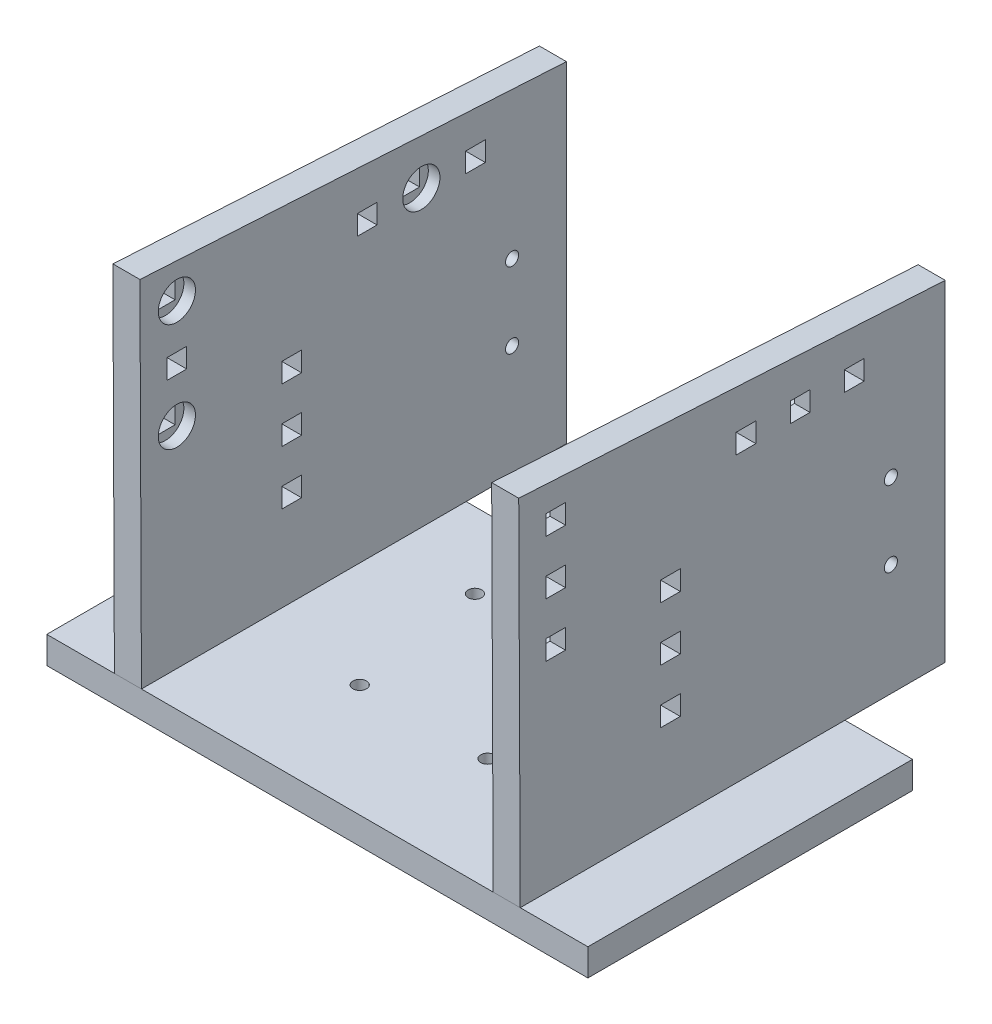
SolidWorks part; units mm, degrees
material "ABS"
ref_plane "Front Plane" through (0, 0, 0) normal (0, 0, 1) x (1, 0, 0)
ref_plane "Top Plane" through (0, 0, 0) normal (0, 1, 0) x (1, 0, 0)
ref_plane "Right Plane" through (0, 0, 0) normal (1, 0, 0) x (0, 0, -1)
sketch "Sketch1" plane through (0, 0, 0) normal (0, 1, 0) x (1, 0, 0)
  line L1 (0, 0) -> (127, 0)
  line L2 (0, 0) -> (0, 76.2)
  line L3 (0, 76.2) -> (127, 76.2)
  line L4 (127, 0) -> (127, 76.2)
  dimension "D1" = 76.2
  dimension "5" = 127
extrude "Boss-Extrude1" add sketch "Sketch1" along normal blind 6.35
ref_plane "Plane2" through (63.5, 0, 0) normal (1, 0, 0) x (0, 0, -1)
ref_plane "Plane3" through (104.775, 0, 0) normal (1, 0, 0) x (0, 0, -1)
sketch "Sketch3" plane through (104.775, 0, 0) normal (1, 0, 0) x (0, 0, -1)
  line L0 (0, 6.35) -> (-0.3556, 89.7636)
  line L1 (0, 6.35) -> (0, 0) construction
  line L2 (-0.3556, 89.7636) -> (99.7458, 83.9978)
  line L3 (99.7458, 83.9978) -> (99.7458, 6.35)
  line L4 (99.7458, 0) -> (101.6, 0) construction
  line L5 (101.6, 0) -> (101.6, 6.35) construction
  line L6 (99.7458, 6.35) -> (0, 6.35)
  line L7 (0, 6.35) -> (76.2, 6.35) construction
  line L8 (86.9864, 32.5968) -> (86.9864, 50.326) construction
  line L9 (5.9944, 58.0136) -> (5.9944, 53.3908)
  line L10 (5.9944, 70.7136) -> (10.6172, 70.7136)
  line L11 (5.9944, 70.7136) -> (5.9944, 66.0908)
  line L12 (5.9944, 66.0908) -> (10.6172, 66.0908)
  line L13 (10.6172, 70.7136) -> (10.6172, 66.0908)
  line L14 (5.9944, 70.7136) -> (10.6172, 66.0908) construction
  line L15 (5.9944, 66.0908) -> (10.6172, 70.7136) construction
  line L16 (32.9352, 43.7728) -> (37.558, 43.7728)
  line L17 (32.9352, 43.7728) -> (32.9352, 39.15)
  line L18 (32.9352, 39.15) -> (37.558, 39.15)
  line L19 (37.558, 43.7728) -> (37.558, 39.15)
  line L20 (32.9352, 43.7728) -> (37.558, 39.15) construction
  line L21 (32.9352, 39.15) -> (37.558, 43.7728) construction
  line L22 (76.073, 77.6478) -> (80.6958, 77.6478)
  line L23 (76.073, 77.6478) -> (76.073, 73.025)
  line L24 (76.073, 73.025) -> (80.6958, 73.025)
  line L25 (80.6958, 77.6478) -> (80.6958, 73.025)
  line L26 (76.073, 77.6478) -> (80.6958, 73.025) construction
  line L27 (76.073, 73.025) -> (80.6958, 77.6478) construction
  line L28 (5.9944, 83.4136) -> (10.6172, 83.4136)
  line L29 (5.9944, 83.4136) -> (5.9944, 78.7908)
  line L30 (5.9944, 78.7908) -> (10.6172, 78.7908)
  line L31 (10.6172, 83.4136) -> (10.6172, 78.7908)
  line L32 (5.9944, 83.4136) -> (10.6172, 78.7908) construction
  line L33 (5.9944, 78.7908) -> (10.6172, 83.4136) construction
  line L34 (5.9944, 58.0136) -> (10.6172, 58.0136)
  line L35 (10.6172, 58.0136) -> (10.6172, 53.3908)
  line L36 (5.9944, 53.3908) -> (10.6172, 53.3908)
  line L37 (32.9352, 56.4728) -> (32.9352, 51.85)
  line L38 (32.9352, 56.4728) -> (37.558, 56.4728)
  line L39 (37.558, 56.4728) -> (37.558, 51.85)
  line L40 (32.9352, 51.85) -> (37.558, 51.85)
  line L41 (32.9352, 43.7728) -> (32.9352, 56.4728) construction
  line L42 (32.9352, 31.0728) -> (32.9352, 26.45)
  line L43 (32.9352, 31.0728) -> (37.558, 31.0728)
  line L44 (37.558, 31.0728) -> (37.558, 26.45)
  line L45 (32.9352, 26.45) -> (37.558, 26.45)
  line L46 (32.9352, 43.7728) -> (32.9352, 31.0728) construction
  line L51 (63.373, 77.6478) -> (63.373, 73.025)
  line L52 (63.373, 77.6478) -> (67.9958, 77.6478)
  line L53 (67.9958, 77.6478) -> (67.9958, 73.025)
  line L54 (63.373, 73.025) -> (67.9958, 73.025)
  line L59 (50.673, 77.6478) -> (50.673, 73.025)
  line L60 (50.673, 77.6478) -> (55.2958, 77.6478)
  line L61 (55.2958, 77.6478) -> (55.2958, 73.025)
  line L62 (50.673, 73.025) -> (55.2958, 73.025)
  line L63 (8.3058, 68.4022) -> (57.1279, 68.4022) construction
  line L64 (7.5352, 43.7728) -> (7.5352, 39.15) [skipped]
  line L65 (7.5352, 39.15) -> (12.158, 39.15) [skipped]
  line L66 (12.158, 43.7728) -> (12.158, 39.15) [skipped]
  line L67 (7.5352, 43.7728) -> (12.158, 43.7728) [skipped]
  line L68 (20.2352, 43.7728) -> (20.2352, 39.15) [skipped]
  line L69 (20.2352, 39.15) -> (24.858, 39.15) [skipped]
  line L70 (24.858, 43.7728) -> (24.858, 39.15) [skipped]
  line L71 (20.2352, 43.7728) -> (24.858, 43.7728) [skipped]
  line L72 (35.2466, 41.4614) -> (8.3058, 68.4022) construction
  line L73 (0, 6.35) -> (99.7458, 6.35)
  line L74 (99.7458, 0) -> (99.7458, 6.35) construction
  line L76 (66.9966, 41.4614) -> (86.9864, 41.4614) construction
  circle A0 centre (8.3058, 68.4022) radius 2.2951 construction
  circle A1 centre (78.3844, 75.3364) radius 2.2951 construction
  circle A2 centre (8.3058, 68.4022) radius 31.75 construction
  circle A3 centre (35.2466, 41.4614) radius 6.35 construction
  circle A4 centre (35.2466, 41.4614) radius 2.2951 construction
  circle A6 centre (35.2466, 41.4614) radius 25.4 construction
  circle A7 centre (66.9966, 41.4614) radius 6.35 construction
  circle A11 centre (86.9864, 50.326) radius 1.5367
  circle A13 centre (86.9864, 32.5968) radius 1.5367
  point P0 (8.3058, 68.4022)
  point P1 (78.3844, 75.3364)
  point P29 (0, 0)
  point P41 (8.3058, 81.1022)
  point P63 (0, 0)
  point P64 (0, 0)
  point P65 (1.9135, 89.7636)
  dimension "D5" = 4.5901
  dimension "D6" = 50.8
  dimension "D12" = 63.5
  dimension "D13" = 12.7
  dimension "D14" = 12.7
  dimension "D15" = 3.0734
  dimension "D16" = 17.7292
  dimension "D18" = 4.6228
  dimension "D1" = 8.3058
  dimension "D2" = 68.4022
  dimension "D3" = 70.0786
  dimension "D4" = 6.9342
  dimension "D7" = 101.6
  dimension "D8" = 19.05
  dimension "D9" = 6.35
  dimension "D10" = 6.35
  dimension "D11" = 6.35
  dimension "D17" = 19.9898
  dimension "D19" = 12.7
  dimension "D21" = 12.7
  dimension "D23" = 12.7
  dimension "D25" = 12.7
  dimension "D27" = 12.7
  dimension "D28" = 45
  dimension "D29" = 0
  dimension "D30" = 6.35
  dimension "D20" = 2
  dimension "D22" = 2
  dimension "D24" = 2
  dimension "D26" = 3
extrude "Boss-Extrude2" add sketch "Sketch3" along normal blind 6.35 contours L6 L73 L3 L2 L0 A13 A11 L28 L31 L30 L29 L22 L25 L24 L23 L16 L19 L18 L17 L10 L13 L12 L11 L36 L9 L34 L35 L40 L37 L38 L39 L45 L42 L43 L44 L54 L51 L52 L53 L62 | A1 | A0 | A4
sketch "Sketch5" plane through (104.775, 0, 0) normal (-1, 0, 0) x (0, 0, 1)
  line L0 (-5.9944, 58.0136) -> (-5.9944, 53.3908) construction
  line L1 (-67.9958, 77.6478) -> (-63.373, 73.025) construction
  line L2 (-63.373, 73.025) -> (-63.373, 77.6478) construction
  line L3 (-63.373, 77.6478) -> (-67.9958, 73.025) construction
  point P0 (-65.6844, 75.3364)
  point P1 (-8.3058, 55.7022)
  point P2 (-8.3058, 81.1022)
  point P7 (-5.9944, 55.7022)
  point P9 (0, 0)
  point P10 (-65.6844, 75.3364)
hole_wizard "CBORE for #8 Button Head Cap Screw1" positions "3DSketch1" profile "Sketch6" counterbore size "#8" standard "ANSI Inch"
sketch3d "3DSketch1"
  line L0 (104.775, 78.7908, -5.9944) -> (104.775, 83.4136, -10.6172) construction
  point P0 (104.775, 75.3364, -65.6844)
  point P3 (104.775, 81.1022, -8.3058)
  point P6 (104.775, 81.1022, -8.3058)
  point P8 (104.775, 55.7022, -8.3058)
  point P11 (104.775, 81.1022, -8.3058)
  point P14 (104.775, 81.1022, -8.3058)
  point P17 (104.775, 81.1022, -8.3058)
  point P19 (104.775, 81.1022, -8.3058)
  point P23 (104.775, 68.4022, -8.3058)
  point P26 (104.775, 81.1022, -8.3058)
  point P29 (104.775, 81.1022, -8.3058)
  point P31 (104.775, 81.1022, -8.3058)
  point P33 (104.775, 81.1022, -8.3058)
  point P35 (104.775, 81.1022, -8.3058)
  point P37 (104.775, 81.1022, -8.3058)
  point P39 (104.775, 81.1022, -8.3058)
  point P41 (104.775, 81.1022, -8.3058)
  point P44 (104.775, 81.1022, -8.3058)
  point P46 (104.775, 81.1022, -8.3058)
sketch "Sketch6" plane through (104.775, 75.3364, -65.6844) normal (0, 1, 0) x (0, 0, 1)
  line L0 (0, 0) -> (0, 22.225)
  line L1 (0, 22.225) -> (2.2479, 22.225)
  line L3 (2.2479, 22.225) -> (2.2479, 2.7178)
  line L4 (2.2479, 2.7178) -> (4.3663, 2.7178)
  line L5 (4.3663, 2.7178) -> (4.3663, 0)
  line L7 (4.3663, 0) -> (0, 0)
  line L11 (0, -6.35) -> (0, 107.95) construction
  dimension "Thru Hole Dia." = 4.4958
  dimension "Thru Hole Depth" = 22.225
  dimension "C'Bore Dia." = 8.7325
  dimension "C'Bore Depth" = 2.7178
mirror "Mirror1" about plane through (63.5, 0, 0) normal (1, 0, 0) of "CBORE for #8 Button Head Cap Screw1", "Boss-Extrude2"
sketch "Sketch4" plane through (0, 0, 0) normal (0, -1, 0) x (1, 0, 0)
  circle A0 centre (76.9997, -26.4488) radius 1.6
  circle A1 centre (47.0003, -26.4488) radius 1.6
  circle A2 centre (81.9993, -58.4842) radius 1.6
  circle A3 centre (42.0007, -58.4842) radius 1.6
  dimension "D1" = 3.2
extrude "Cut-Extrude1" cut sketch "Sketch4" against normal through all
